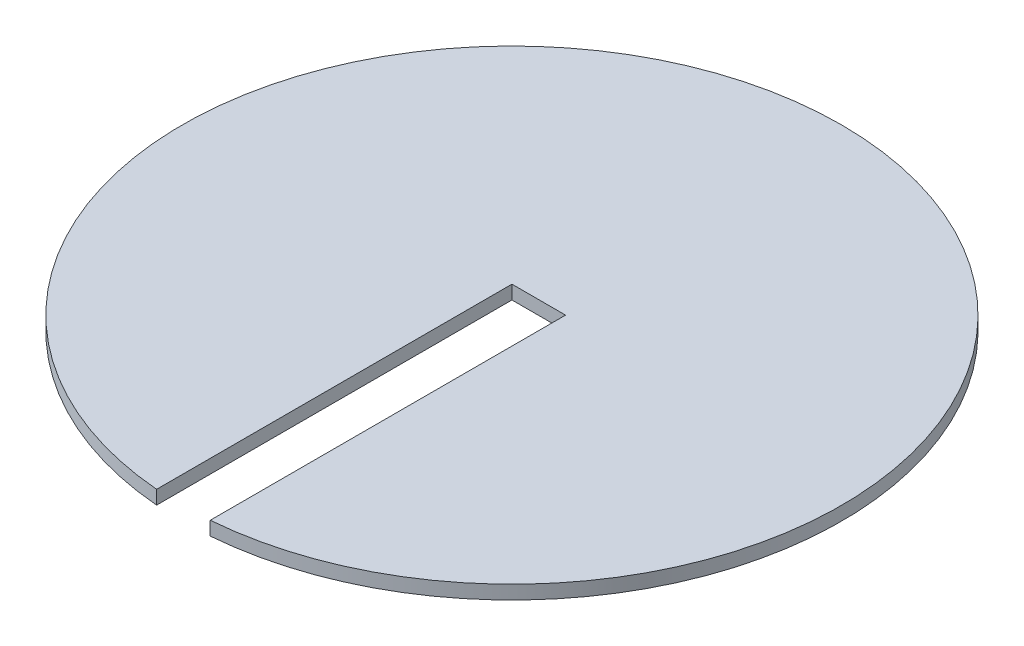
SolidWorks part; units mm, degrees
material "Custom Plastic"
ref_plane "Front Plane" through (0, 0, 0) normal (0, 0, 1) x (1, 0, 0)
ref_plane "Top Plane" through (0, 0, 0) normal (0, 1, 0) x (1, 0, 0)
ref_plane "Right Plane" through (0, 0, 0) normal (1, 0, 0) x (0, 0, -1)
sketch "Sketch1" plane through (0, 0, 0) normal (0, 1, 0) x (1, 0, 0)
  line L0 (2.4085, 1.9486) -> (2.4085, -32.9251)
  line L1 (8.6085, 8.1486) -> (2.4085, 8.1486)
  line L2 (8.6085, 8.1486) -> (8.6085, 1.9486)
  line L3 (8.6085, 1.9486) -> (8.6085, -32.9251)
  line L4 (2.4085, 8.1486) -> (2.4085, 1.9486)
  line L5 (8.6085, 8.1486) -> (2.4085, 1.9486) construction
  line L6 (8.6085, 1.9486) -> (2.4085, 8.1486) construction
  line L7 (-15.8231, 5.0486) -> (5.5085, 5.0486) construction
  arc A0 (8.6085, -32.9251) -> (2.4085, -32.9251) centre (5.5085, 5.0486) ccw
  point P0 (0, 0)
  dimension "D1" = 76.2
  dimension "D2" = 6.2
  dimension "D3" = 6.2
extrude "Boss-Extrude1" add sketch "Sketch1" along normal blind 1.5875
